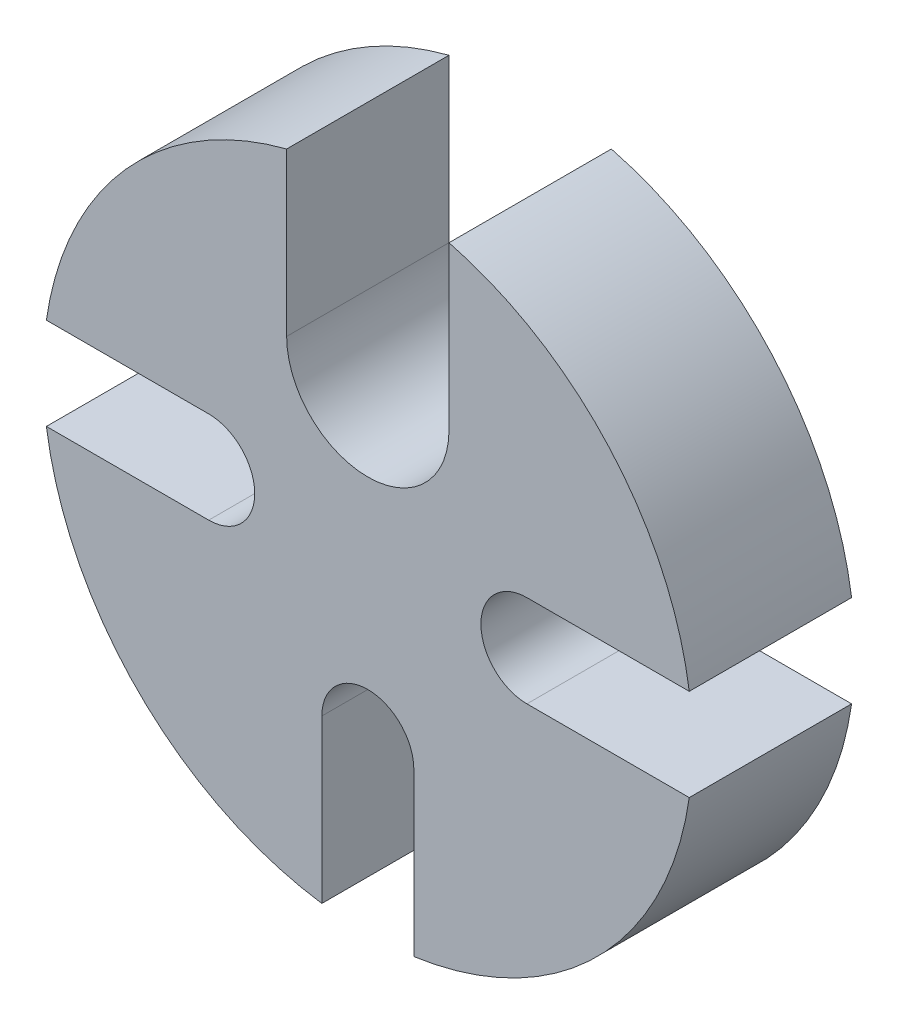
SolidWorks part; units mm, degrees
material "201 Annealed Stainless Steel (SS)"
ref_plane "Front Plane" through (0, 0, 0) normal (0, 0, 1) x (1, 0, 0)
ref_plane "Top Plane" through (0, 0, 0) normal (0, 1, 0) x (1, 0, 0)
ref_plane "Right Plane" through (0, 0, 0) normal (1, 0, 0) x (0, 0, -1)
sketch "Sketch1" plane through (0, 0, 0) normal (0, 1, 0) x (1, 0, 0)
  line L0 (1524, 0) -> (0, 0)
  line L1 (0, 0) -> (0, -762)
  line L2 (0, -762) -> (1524, -762)
  line L3 (1524, -762) -> (1524, 0)
  line L4 (0, 0) -> (0, -762) construction
revolve "Revolve1" add sketch "Sketch1" angle 360 about L4
sketch "Sketch2" plane through (0, 0, 0) normal (0, 0, -1) x (-1, 0, 0)
  line L0 (215.9, -1508.6296) -> (215.9, -746.76)
  line L1 (-215.9, -746.76) -> (-215.9, -1508.6296)
  arc A0 (-215.9, -1508.6296) -> (215.9, -1508.6296) centre (0, 0) ccw
  arc A1 (215.9, -746.76) -> (-215.9, -746.76) centre (0, -746.76) ccw
extrude "Cut-Extrude1" cut sketch "Sketch2" against normal through all
sketch "Sketch3" plane through (0, 0, 0) normal (0, 0, -1) x (-1, 0, 0)
  line L0 (-1508.6296, -215.9) -> (-746.76, -215.9)
  line L1 (-746.76, 215.9) -> (-1508.6296, 215.9)
  arc A0 (-1508.6296, 215.9) -> (-1508.6296, -215.9) centre (0, 0) ccw
  arc A1 (-746.76, -215.9) -> (-746.76, 215.9) centre (-746.76, 0) ccw
extrude "Cut-Extrude2" cut sketch "Sketch3" against normal through all
sketch "Sketch4" plane through (0, 0, 0) normal (0, 0, -1) x (-1, 0, 0)
  line L0 (-381, 1475.6067) -> (-381, 713.74)
  line L1 (381, 713.74) -> (381, 1475.6067)
  arc A0 (381, 1475.6067) -> (-381, 1475.6067) centre (0, 0) ccw
  arc A1 (-381, 713.74) -> (381, 713.74) centre (0, 713.74) ccw
extrude "Cut-Extrude3" cut sketch "Sketch4" against normal through all
sketch "Sketch5" plane through (0, 0, 0) normal (0, 0, -1) x (-1, 0, 0)
  line L0 (1508.6296, 215.9) -> (746.76, 215.9)
  line L1 (746.76, -215.9) -> (1508.6296, -215.9)
  arc A0 (1508.6296, -215.9) -> (1508.6296, 215.9) centre (0, 0) ccw
  arc A1 (746.76, 215.9) -> (746.76, -215.9) centre (746.76, 0) ccw
extrude "Cut-Extrude4" cut sketch "Sketch5" against normal through all
ref_plane "Plane1" through (0, 0, 0) normal (0, -1, 0) x (1, 0, 0)
sketch "Sketch6" plane through (0, 0, 0) normal (0, -1, 0) x (1, 0, 0)
  line L0 (50.8, 0) -> (0, 0)
  line L1 (0, 0) -> (0, -762)
  line L2 (0, -762) -> (50.8, -762)
  line L3 (50.8, -762) -> (50.8, 0)
  line L4 (0, 0) -> (0, -762) construction
revolve "Revolve2" add sketch "Sketch6" angle 360 about L4
